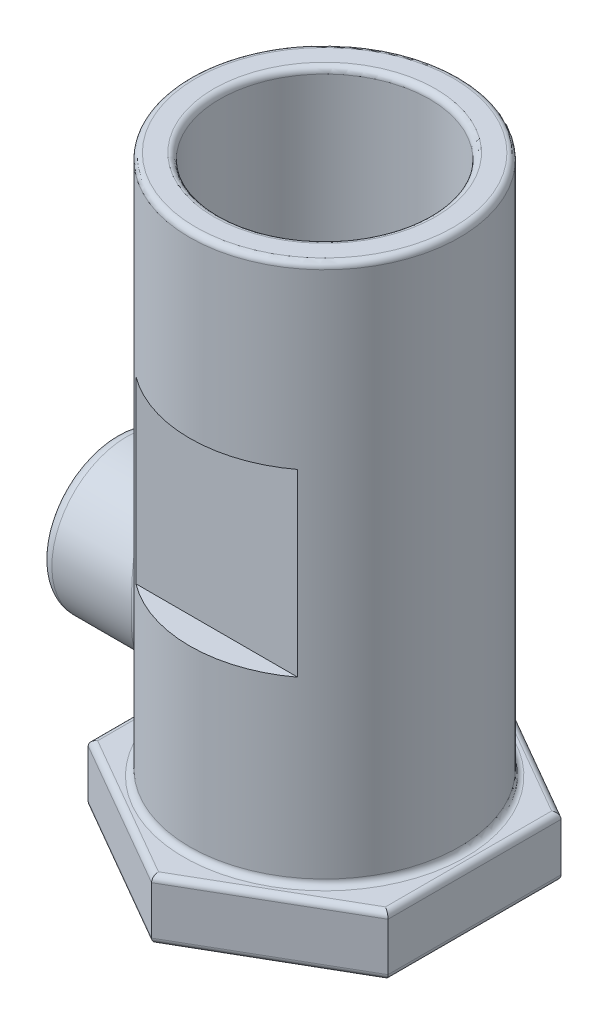
SolidWorks part; units mm, degrees
other "Markup1"
sketch "Sketch1" plane through (0, 0, 0) normal (0.5774, 0.5773, 0.5774) x (0.7071, 0, -0.7071)
sketch "Sketch2" plane through (0, 0, 0) normal (0.5774, 0.5773, 0.5774) x (0.7071, 0, -0.7071)
ref_plane "Front (z)" through (0, 0, 0) normal (0, 0, 1) x (1, 0, 0)
ref_plane "Top (y)" through (0, 0, 0) normal (0, 1, 0) x (1, 0, 0)
ref_plane "Right (x)" through (0, 0, 0) normal (1, 0, 0) x (0, 0, -1)
sketch "Sketch5" plane through (0, 0, 0) normal (0, 1, 0) x (1, 0, 0)
  circle A0 centre (0, 0) radius 8.75
  circle A1 centre (0, 0) radius 11.25
  dimension "D1" = 17.5
  dimension "D2" = 22.5
extrude "Boss-Extrude3" add sketch "Sketch5" along normal blind 50
sketch "Sketch6" plane through (0, 0, 0) normal (0, -1, 0) x (1, 0, 0)
  line L1 (0, 14.4338) -> (-12.5, 7.2169)
  line L2 (-12.5, 7.2169) -> (-12.5, -7.2169)
  line L3 (-12.5, -7.2169) -> (0, -14.4338)
  line L4 (0, -14.4338) -> (12.5, -7.2169)
  line L5 (12.5, -7.2169) -> (12.5, 7.2169)
  line L6 (12.5, 7.2169) -> (0, 14.4338)
  circle A0 centre (0, 0) radius 12.5 construction
  circle A1 centre (0, 0) radius 8.75 construction
  circle A2 centre (0, 0) radius 8.75
  dimension "D1" = 25
extrude "Boss-Extrude4" add sketch "Sketch6" against normal blind 5
fillet "Fillet1" radius 0.5 15 edges at (0, 50, 11.25) (0, 50, 8.75) (-12.5, 0, 0) (-6.25, 0, -10.8253) (6.25, 0, -10.8253) (12.5, 0, 0) (6.25, 0, 10.8253) (-6.25, 0, 10.8253) (-6.25, 5, -10.8253) (6.25, 5, -10.8253) (12.5, 5, 0) (6.25, 5, 10.8253) (-6.25, 5, 10.8253) (-12.5, 5, 0) (0, 5, -11.25)
ref_plane "Plane1" through (-11.25, 0, 0) normal (-1, 0, 0) x (0, 0, 1)
ref_plane "Plane2" through (-17.5, 0, 0) normal (1, 0, 0) x (0, 0, -1)
sketch "Sketch16" plane through (-17.5, 0, 0) normal (1, 0, 0) x (0, 0, -1)
  circle A0 centre (0, 15) radius 6.25
  dimension "D1" = 12.5
  dimension "D2" = 15
extrude "Boss-Extrude6" add sketch "Sketch16" along normal up to surface (8.1458 mm away)
hole_wizard "CBORE for M4 SBHCS1" positions "Sketch9" profile "Sketch10" counterbore size "M4" standard "ANSI Metric"
sketch "Sketch9" plane through (-17.5, 0, 0) normal (-1, 0, 0) x (0, 0, 1)
  point P0 (0, 15)
  dimension "D1" = 15
sketch "Sketch10" plane through (-17.5, 15, 0) normal (0, 1, 0) x (0, 0, 1)
  line L0 (0, 0) -> (0, 10.9013)
  line L1 (0, 10.9013) -> (1.5, 10)
  line L2 (1.5, 10) -> (1.5, 2.2)
  line L3 (1.5, 2.2) -> (4.3, 2.2)
  line L4 (4.3, 2.2) -> (4.3, 0)
  line L5 (4.3, 0) -> (0, 0)
  line L10 (0, 10.9013) -> (-1.5, 10) construction
  line L11 (0, -6.35) -> (0, 107.95) construction
  dimension "Hole Dia." = 3
  dimension "Hole Depth" = 10
  dimension "C'Bore Dia." = 8.6
  dimension "C'Bore Depth" = 2.2
  dimension "Drill Angle" = 118
sketch "Sketch11" plane through (0, 0, 0) normal (1, 0, 0) x (0, 0, -1)
  line L0 (-11.25, 49.5) -> (-11.25, 5.5) construction
  line L1 (-11.25, 35) -> (-9, 35)
  line L2 (-11.25, 35) -> (-11.25, 20)
  line L3 (-11.25, 20) -> (-9, 20)
  line L4 (-9, 35) -> (-9, 20)
  line L5 (11.25, 5.5) -> (11.25, 49.5) construction
  line L6 (11.25, 20) -> (9, 20)
  line L7 (11.25, 20) -> (11.25, 35)
  line L8 (11.25, 35) -> (9, 35)
  line L9 (9, 20) -> (9, 35)
  dimension "D1" = 15
  dimension "D2" = 15
  dimension "D3" = 2.25
  dimension "D4" = 20
extrude "Cut-Extrude1" cut sketch "Sketch11" against normal through all both and the other way through all
hole_wizard "M4x0.7 Tapped Hole1" positions "Sketch12" profile "Sketch13" tap size "M4x0.7" standard "ANSI Metric"
sketch "Sketch12" plane through (-15.3, 0, 0) normal (-1, 0, 0) x (0, 0, 1)
  point P0 (0, 15)
sketch "Sketch13" plane through (-15.3, 15, 0) normal (0, 1, 0) x (0, 0, 1)
  line L0 (0, 0) -> (0, 11.0914)
  line L1 (0, 11.0914) -> (1.65, 10.1)
  line L2 (1.65, 10.1) -> (1.65, 0)
  line L5 (1.65, 0) -> (0, 0)
  line L10 (0, 11.0914) -> (-1.65, 10.1) construction
  line L11 (0, -6.35) -> (0, 107.95) construction
  dimension "Tap Drill Dia." = 3.3
  dimension "Tap Drill Depth" = 10.1
  dimension "Drill Angle" = 118
cosmetic thread "Hole Thread2" parameters "D1"=8, "D2"=4.3
fillet "Fillet3" radius 1 2 edges at (-17.5, 15, -6.25) (-9.3684, 14.4835, -6.2286)
